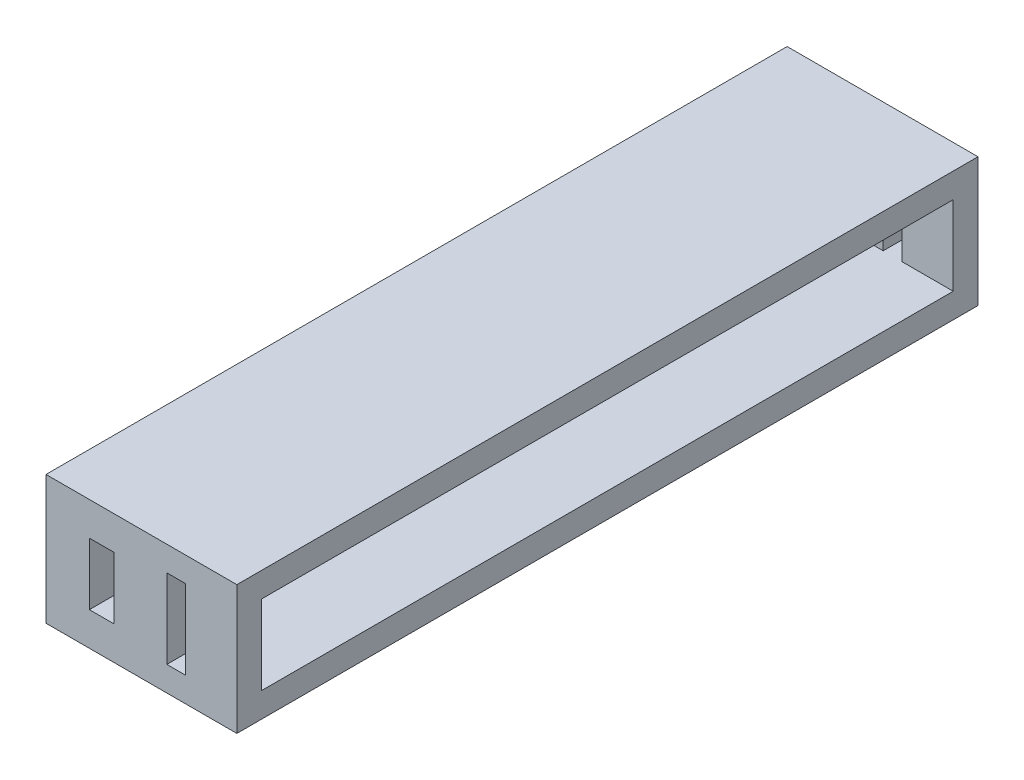
SolidWorks part; units mm, degrees
material "ABS"
ref_plane "Front Plane" through (0, 0, 0) normal (0, 0, 1) x (1, 0, 0)
ref_plane "Top Plane" through (0, 0, 0) normal (0, 1, 0) x (1, 0, 0)
ref_plane "Right Plane" through (0, 0, 0) normal (1, 0, 0) x (0, 0, -1)
sketch "Sketch2" plane through (0, 0, 0) normal (1, 0, 0) x (0, 0, -1)
  line L1 (0, 0) -> (111.6, 0)
  line L2 (0, 0) -> (0, 12.8)
  line L3 (0, 12.8) -> (111.6, 12.8)
  line L4 (111.6, 0) -> (111.6, 12.8)
  dimension "D1" = 12.8
  dimension "D2" = 111.6
extrude "arm" add sketch "Sketch2" along normal mid plane 26.8
shell "shell" thickness 4
sketch "Sketch3" plane through (-17.4, 0, 0) normal (-1, 0, 0) x (0, 0, 1)
  line L0 (4, 6.4) -> (-49996, 6.4) construction
  line L1 (4, 16.8) -> (4, -4) construction
  line L2 (0, 12.8) -> (0, 0) construction
  line L3 (0, 12.8) -> (0, 0) construction
  circle A0 centre (-5.8, 6.4) radius 2.5
  point P4 (4, 6.4)
  dimension "D2" = 5
  dimension "D1" = 5.8
extrude "pivot peg hole" cut sketch "Sketch3" against normal up to next
sketch "Sketch4" plane through (0, 0, 4) normal (0, 0, 1) x (1, 0, 0)
  line L0 (-13.4, 6.4) -> (13.4, 6.4) construction
  line L1 (2.1, 12.8) -> (5.1, 12.8)
  line L2 (2.1, 12.8) -> (2.1, 0)
  line L3 (2.1, 0) -> (5.1, 0)
  line L4 (-13.4, 12.8) -> (-13.4, 0)
  line L5 (13.4, 12.8) -> (-13.4, 12.8)
  line L6 (13.4, 0) -> (13.4, 12.8)
  line L7 (-13.4, 0) -> (13.4, 0)
  line L8 (-13.4, 12.8) -> (-13.4, 0) construction
  line L9 (13.4, 12.8) -> (-13.4, 12.8) construction
  line L10 (13.4, 0) -> (13.4, 12.8) construction
  line L11 (-13.4, 0) -> (13.4, 0) construction
  line L12 (5.1, 12.8) -> (5.1, 0)
  line L14 (-10.4, 1.4) -> (-6.4, 1.4)
  line L15 (-10.4, 1.4) -> (-10.4, 11.4)
  line L16 (-10.4, 11.4) -> (-6.4, 11.4)
  line L17 (-6.4, 1.4) -> (-6.4, 11.4)
  line L18 (-10.4, 1.4) -> (-6.4, 11.4) construction
  line L19 (-10.4, 11.4) -> (-6.4, 1.4) construction
  point P10 (-8.4, 6.4)
  dimension "D2" = 15.5
  dimension "D3" = 3
  dimension "D4" = 3
  dimension "D5" = 4
  dimension "D6" = 10
extrude "cable passthrough" cut sketch "Sketch4" against normal up to next
ref_plane "arm mid plane" through (0, 0, -55.8) normal (0, 0, 1) x (1, 0, 0)
mirror "elbow mount" about plane through (0, 0, -55.8) normal (0, 0, 1) of "cable passthrough", "pivot peg hole"
equation "\"servo_width\"= 22.5mm"
equation "\"servo_height\"= 22.6mm"
equation "\"servo_thickness\"= 12.8mm"
equation "\"servo_tabs_from_base\" = 15.5mm"
equation "\"servo_tab_thickness\"= 3mm"
equation "\"wall_thickness\"= 4mm"
equation "\"D1@arm\"=\"servo_width\"+4.3"
equation "\"D1@shell\" = \"wall_thickness\""
equation "\"D1@Sketch2\"=\"servo_thickness\""
equation "\"D2@Sketch3\"=2.5*2"
equation "\"D1@Sketch3\"=5.8mm"
equation "\"D2@Sketch4\"=\"servo_tabs_from_base\""
equation "\"D3@Sketch4\"=\"servo_tab_thickness\""
